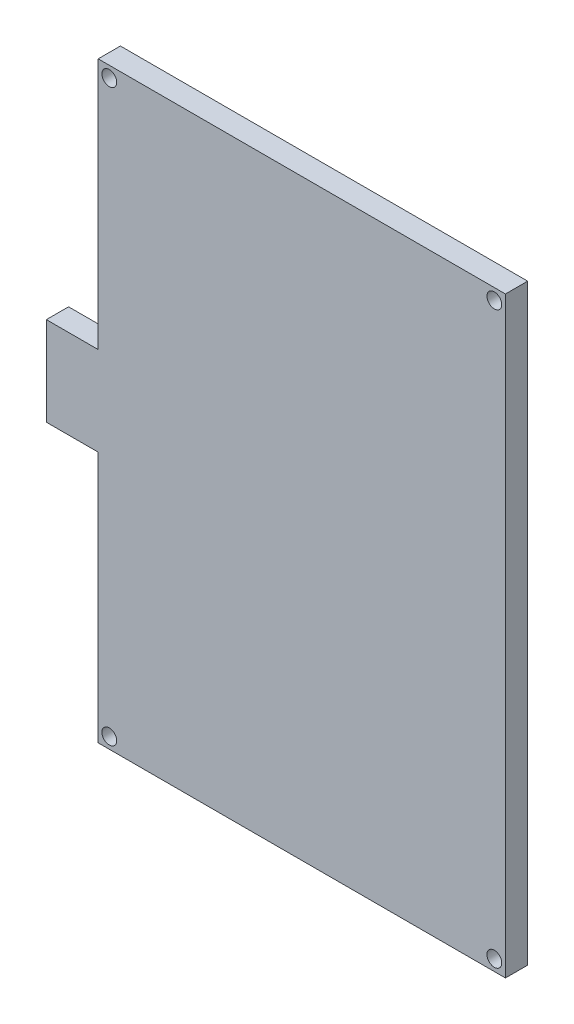
SolidWorks part; units mm, degrees
ref_plane "Front Plane" through (0, 0, 0) normal (0, 0, 1) x (1, 0, 0)
ref_plane "Top Plane" through (0, 0, 0) normal (0, 1, 0) x (1, 0, 0)
ref_plane "Right Plane" through (0, 0, 0) normal (1, 0, 0) x (0, 0, -1)
sketch "Sketch1" plane through (0, 0, 0) normal (0, 0, 1) x (1, 0, 0)
  line L1 (-27.5, 40) -> (27.5, 40)
  line L2 (-27.5, 40) -> (-27.5, 6)
  line L3 (-27.5, -40) -> (27.5, -40)
  line L4 (27.5, 40) -> (27.5, -40)
  line L5 (-27.5, 40) -> (27.5, -40) construction
  line L6 (-27.5, -40) -> (27.5, 40) construction
  line L7 (-27.5, 40) -> (-27.5, 6)
  line L9 (-27.5, 6) -> (-34.5, 6)
  line L10 (-34.5, 6) -> (-34.5, -6)
  line L11 (-34.5, -6) -> (-27.5, -6)
  line L12 (-27.5, -6) -> (-27.5, -40)
  point P0 (0, 0)
  dimension "D1" = 55
  dimension "D2" = 80
  dimension "D3" = 34
  dimension "D4" = 7
  dimension "D5" = 12
extrude "Boss-Extrude1" add sketch "Sketch1" against normal blind 3 contours L11 L12 L3 L4 L1 L2 L9 L10
sketch "Sketch2" plane through (0, 0, 0) normal (0, 0, 1) x (1, 0, 0)
  line L0 (-27.5, 40) -> (-24.5, 37)
  line L1 (27.5, 40) -> (24.5, 37)
  line L2 (-24.5, -37) -> (-27.5, -40)
  line L3 (27.5, -40) -> (24.5, -37)
  circle A0 centre (-26, -38.5) radius 1
  circle A1 centre (26, -38.5) radius 1
  circle A2 centre (26, 38.5) radius 1
  circle A3 centre (-26, 38.5) radius 1
  dimension "D1" = 2
extrude "Cut-Extrude1" cut sketch "Sketch2" against normal blind 56 contours A2 | A3 | A0 | A1
